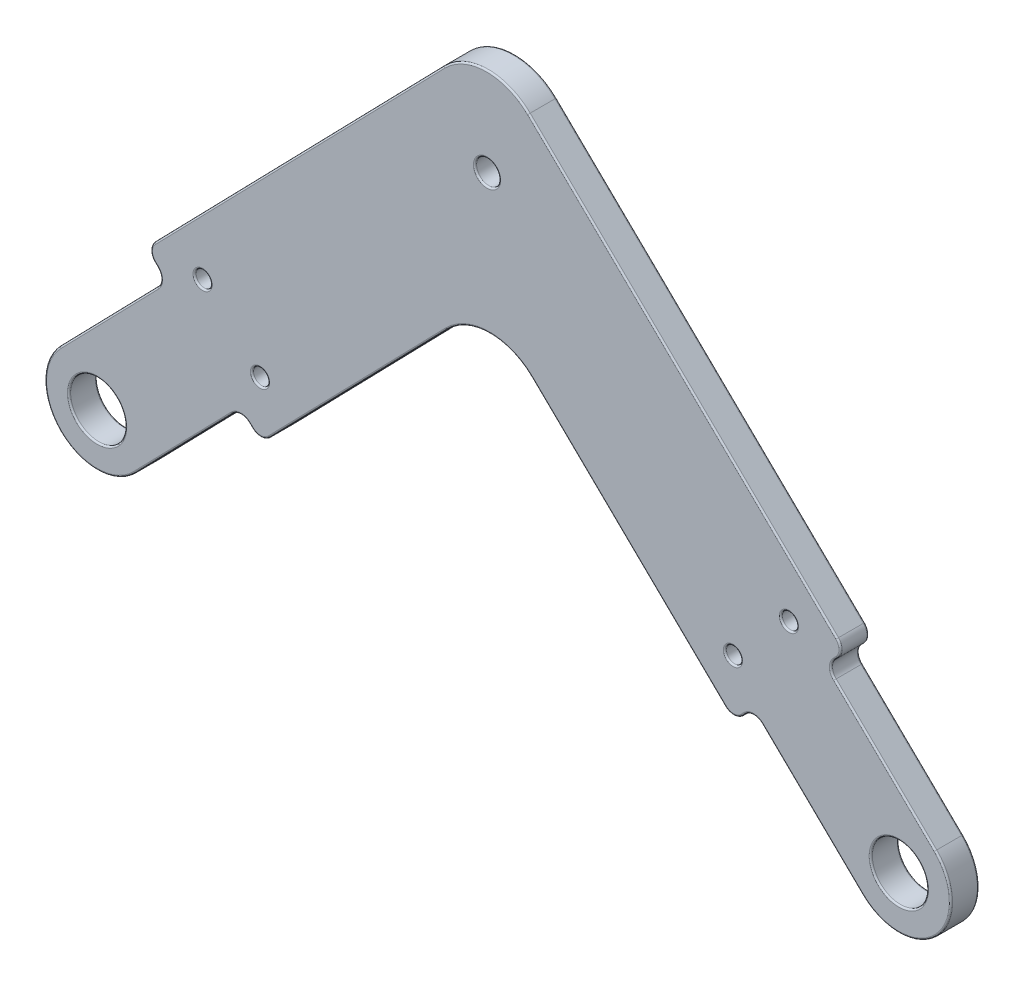
SolidWorks part; units mm, degrees
ref_plane "Front Plane" through (0, 0, 0) normal (0, 0, 1) x (1, 0, 0)
ref_plane "Top Plane" through (0, 0, 0) normal (0, 1, 0) x (1, 0, 0)
ref_plane "Right Plane" through (0, 0, 0) normal (1, 0, 0) x (0, 0, -1)
sketch "Sketch2" plane through (0, 0, 0) normal (0, 0, 1) x (1, 0, 0)
  line L0 (-2.7226, 99.9629) -> (-100, 0) construction
  line L1 (-100, 0) -> (100, 0) construction
  line L2 (100, 0) -> (-2.7226, 99.9629) construction
  line L3 (0, 0) -> (-51.3613, 49.9815) construction
  line L4 (-41.6336, 59.9778) -> (38.3664, 59.9778) construction
  line L5 (-2.7226, 99.9629) -> (-2.7226, 59.9778) construction
  circle A0 centre (-100, 0) radius 20
  circle A1 centre (0, 0) radius 20
  circle A2 centre (100, 0) radius 20
  point P2 (0, 0)
  dimension "D5" = 40
  dimension "D1" = 90
  dimension "D2" = 200
  dimension "D3" = 90
  dimension "D4" = 80
sketch "Sketch3" plane through (0, 0, 0) normal (0, 0, 1) x (1, 0, 0)
  line L0 (-57.8679, 43.2952) -> (-41.6336, 59.9778) construction
  line L1 (-2.7226, 99.9629) -> (-100, 0) construction
  line L2 (-41.6336, 59.9778) -> (38.3664, 59.9778) construction
  line L3 (38.3664, 59.9778) -> (86.3833, 13.2509) construction
  line L4 (100, 0) -> (-2.7226, 99.9629) construction
  line L5 (-50.7012, 36.3211) -> (-37.4115, 49.9778)
  line L6 (-37.4115, 49.9778) -> (34.3038, 49.9778)
  line L7 (34.3038, 49.9778) -> (79.4092, 6.0842)
  line L8 (-65.0346, 50.2694) -> (-45.8557, 69.9778)
  line L9 (-45.8557, 69.9778) -> (42.429, 69.9778)
  line L10 (42.429, 69.9778) -> (93.3574, 20.4176)
  line L11 (-65.0346, 50.2694) -> (-50.7012, 36.3211)
  line L12 (93.3574, 20.4176) -> (79.4092, 6.0842)
  line L13 (90.9165, 17.9092) -> (104.5332, 4.6583)
  line L14 (81.8501, 8.5925) -> (95.4668, -4.6583)
  line L15 (89.7741, 23.9046) -> (75.8258, 9.5713) construction
  line L16 (-2.7226, 99.9629) -> (-2.7226, 59.9778) construction
  line L17 (3.2774, 69.9778) -> (0.7302, 85.3403)
  line L18 (-8.7226, 69.9778) -> (-6.1755, 85.3403)
  circle A0 centre (100, 0) radius 3.5
  circle A1 centre (100, 0) radius 10 construction
  arc A2 (95.4668, -4.6583) -> (104.5332, 4.6583) centre (100, 0) ccw
  circle A3 centre (100, 0) radius 6.5 construction
  circle A4 centre (79.3129, 13.1546) radius 1
  circle A5 centre (86.287, 20.3213) radius 1
  circle A6 centre (-2.7226, 59.9778) radius 1.5
  circle A7 centre (-2.7226, 84.7678) radius 1.5
  arc A8 (0.7302, 85.3403) -> (-6.1755, 85.3403) centre (-2.7226, 84.7678) ccw
  circle A9 centre (-2.7226, 84.7678) radius 3.5 construction
  circle A10 centre (-51.3613, 49.9815) radius 1.5
  dimension "D4" = 20
  dimension "D5" = 7
  dimension "D12" = 2
  dimension "D13" = 2
  dimension "D14" = 3
  dimension "D19" = 3
  dimension "D3" = 27.5
  dimension "D7" = 19
  dimension "D8" = 5
  dimension "D9" = 10
  dimension "D10" = 5
  dimension "D11" = 5
  dimension "D15" = 14.79
  dimension "D17" = 6
  dimension "D18" = 6
  dimension "D1" = 10
  dimension "D2" = 10
  dimension "D6" = 3
  dimension "D16" = 2
sketch "Sketch4" plane through (0, 0, 0) normal (0, 0, 1) x (1, 0, 0)
  line L0 (-88.3212, 12.0012) -> (-51.3613, 49.9815) construction
  line L1 (-2.7226, 99.9629) -> (-100, 0) construction
  line L2 (-51.3613, 49.9815) -> (-13.6167, 13.2509) construction
  line L3 (0, 0) -> (-51.3613, 49.9815) construction
  line L4 (-79.5824, 6.6426) -> (-51.1688, 35.8406)
  line L5 (-51.1688, 35.8406) -> (-20.5908, 6.0842)
  line L6 (-93.9158, 20.5908) -> (-51.5539, 64.1223)
  line L7 (-51.5539, 64.1223) -> (-6.6426, 20.4176)
  line L8 (-95.4879, 18.9754) -> (-51.5539, 64.1223) construction
  line L9 (-81.1545, 5.0271) -> (-51.1688, 35.8406) construction
  line L10 (-93.9158, 20.5908) -> (-91.4075, 18.1499)
  line L11 (-6.6426, 20.4176) -> (-9.0835, 17.9092)
  line L12 (-91.4075, 18.1499) -> (-104.6583, 4.5332)
  line L13 (-82.0908, 9.0835) -> (-95.3417, -4.5332)
  line L14 (-9.0835, 17.9092) -> (4.5332, 4.6583)
  line L15 (-18.1499, 8.5925) -> (-4.5332, -4.6583)
  line L16 (-90.4287, 24.1742) -> (-76.0954, 10.2259) construction
  line L17 (-10.2259, 23.9046) -> (-24.1742, 9.5713) construction
  line L18 (-82.0908, 9.0835) -> (-79.5824, 6.6426)
  line L19 (-18.1499, 8.5925) -> (-20.5908, 6.0842)
  circle A0 centre (-100, 0) radius 10 construction
  circle A1 centre (0, 0) radius 3.5
  circle A2 centre (0, 0) radius 10 construction
  circle A3 centre (-100, 0) radius 3.5
  arc A4 (-104.6583, 4.5332) -> (-95.3417, -4.5332) centre (-100, 0) ccw
  arc A5 (-4.5332, -4.6583) -> (4.5332, 4.6583) centre (0, 0) ccw
  circle A6 centre (-100, 0) radius 6.5 construction
  circle A7 centre (0, 0) radius 6.5 construction
  circle A8 centre (-86.8454, 20.6871) radius 1
  circle A9 centre (-79.6787, 13.713) radius 1
  circle A10 centre (-20.6871, 13.1546) radius 1
  circle A11 centre (-13.713, 20.3213) radius 1
  dimension "D1" = 20
  dimension "D2" = 7
  dimension "D3" = 7
  dimension "D9" = 5
  dimension "D13" = 2
  dimension "D7" = 19
  dimension "D8" = 19
  dimension "D10" = 5
  dimension "D11" = 5
  dimension "D12" = 5
  dimension "D14" = 5
  dimension "D15" = 5
  dimension "D4" = 3
  dimension "D5" = 10
  dimension "D6" = 10
sketch "Sketch5" plane through (0, 0, 0) normal (0, 0, 1) x (1, 0, 0)
  line L3 (-59.1493, 83.2714) -> (-59.1493, 93.2714)
  line L5 (55.7226, 83.2714) -> (42.429, 69.9778)
  line L6 (42.429, 69.9778) -> (-45.8557, 69.9778)
  line L7 (-45.8557, 69.9778) -> (-59.1493, 83.2714)
  line L8 (55.7226, 83.2714) -> (55.7226, 93.2714)
  line L9 (-59.1493, 93.2714) -> (55.7226, 93.2714)
  line L10 (-6.7226, 59.9778) -> (-6.7226, 69.9778)
  line L11 (1.2774, 59.9778) -> (1.2774, 69.9778)
  line L12 (-25.2226, 84.7714) -> (19.7774, 84.7714) construction
  line L13 (-25.2226, 89.2714) -> (19.7774, 89.2714)
  line L14 (-25.2226, 80.2714) -> (19.7774, 80.2714)
  circle A0 centre (-2.7226, 59.9778) radius 1.5 construction
  circle A1 centre (-2.7226, 59.9778) radius 1.5
  circle A2 centre (-2.7226, 59.9778) radius 4
  arc A3 (-25.2226, 89.2714) -> (-25.2226, 80.2714) centre (-25.2226, 84.7714) ccw
  arc A4 (19.7774, 80.2714) -> (19.7774, 89.2714) centre (19.7774, 84.7714) ccw
  point P4 (-2.7226, 99.9629)
  point P22 (-2.7226, 84.7714)
  dimension "D1" = 4
  dimension "D3" = 18.8
  dimension "D4" = 18.8
  dimension "D5" = 10
  dimension "D6" = 10
  dimension "D8" = 45
  dimension "D9" = 9
  dimension "D7" = 2.5
extrude "Boss-Extrude1" add sketch "Sketch4" along normal blind 3.5
sketch "Sketch6" plane through (0, 0, 3.5) normal (0, 0, 1) x (1, 0, 0)
  circle A0 centre (-51.3613, 49.9815) radius 1.5
extrude "Cut-Extrude1" cut sketch "Sketch6" against normal blind 3.5
fillet "Fillet1" radius 7.5 2 edges at (-51.1688, 35.8406, 1.75) (-51.5539, 64.1223, 1.75)
fillet "Fillet2" radius 1.5 8 edges at (-6.6426, 20.4176, 1.75) (-9.0835, 17.9092, 1.75) (-18.1499, 8.5925, 1.75) (-20.5908, 6.0842, 1.75) (-79.5824, 6.6426, 1.75) (-82.0908, 9.0835, 1.75) (-91.4075, 18.1499, 1.75) (-93.9158, 20.5908, 1.75)
fillet "Fillet3" radius 0.2 62 edges at (-49.8613, 49.9815, 3.5) (-49.8613, 49.9815, 0) (-12.713, 20.3213, 0) (-12.713, 20.3213, 3.5) (-19.6871, 13.1546, 0) (-19.6871, 13.1546, 3.5) (-78.6787, 13.713, 0) (-78.6787, 13.713, 3.5) (-85.8454, 20.6871, 0) (-85.8454, 20.6871, 3.5) (-96.5, 0, 0) (-96.5, 0, 3.5) (3.5, 0, 0) (3.5, 0, 3.5) (-80.8366, 7.863, 0) (-67.4679, 19.0916, 0) (-33.7298, 18.8702, 0) (-19.3704, 7.3384, 0) (-10.804, 1.444, 0) (4.6583, -4.5332, 0) (-1.7377, 10.7607, 0) (-7.863, 19.1634, 0) (-74.8271, 40.2066, 0) (-92.6616, 19.3704, 0) (-98.556, 10.804, 0) (-104.5332, -4.6583, 0) (-89.2393, 1.7377, 0) (-80.8366, 7.863, 3.5) (-67.4679, 19.0916, 3.5) (-33.7298, 18.8702, 3.5) (-19.3704, 7.3384, 3.5) (-10.804, 1.444, 3.5) (4.6583, -4.5332, 3.5) (-1.7377, 10.7607, 3.5) (-7.863, 19.1634, 3.5) (-74.8271, 40.2066, 3.5) (-92.6616, 19.3704, 3.5) (-98.556, 10.804, 3.5) (-104.5332, -4.6583, 3.5) (-89.2393, 1.7377, 3.5) (-51.5116, 61.016, 0) (-51.5116, 61.016, 3.5) (-51.1265, 32.7343, 0) (-51.1265, 32.7343, 3.5) (-93.2945, 20.5993, 0) (-79.5909, 7.2638, 0) (-20.5993, 6.7055, 0) (-7.2638, 20.4091, 0) (-93.2945, 20.5993, 3.5) (-79.5909, 7.2638, 3.5) (-20.5993, 6.7055, 3.5) (-7.2638, 20.4091, 3.5) (-8.4622, 17.9177, 0) (-8.4622, 17.9177, 3.5) (-18.1414, 7.9713, 0) (-18.1414, 7.9713, 3.5) (-82.0823, 8.4622, 0) (-82.0823, 8.4622, 3.5) (-92.0287, 18.1414, 0) (-92.0287, 18.1414, 3.5) (-26.9482, 40.1777, 0) (-26.9482, 40.1777, 3.5)
